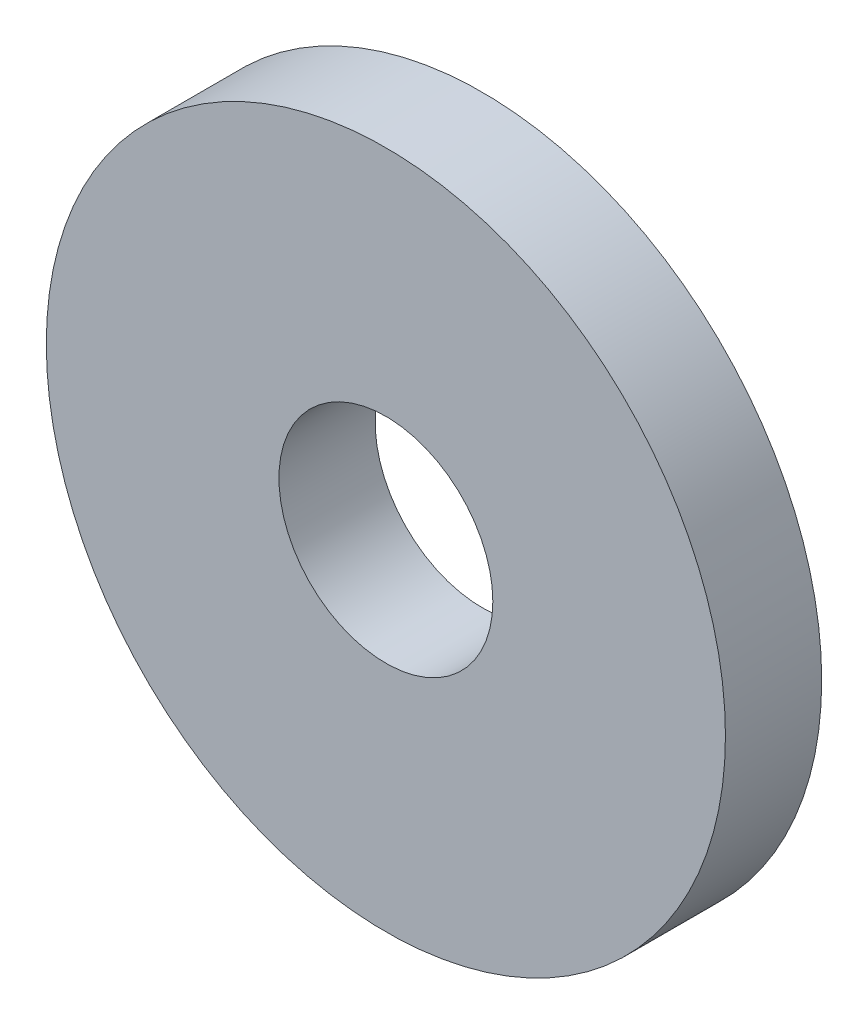
SolidWorks part; units mm, degrees
ref_plane "Front Plane" through (0, 0, 0) normal (0, 0, 1) x (1, 0, 0)
ref_plane "Top Plane" through (0, 0, 0) normal (0, 1, 0) x (1, 0, 0)
ref_plane "Right Plane" through (0, 0, 0) normal (1, 0, 0) x (0, 0, -1)
sketch "Sketch1" plane through (0, 0, 0) normal (0, 0, 1) x (1, 0, 0)
  circle A0 centre (0, 0) radius 15.875
  circle A1 centre (0, 0) radius 5
  dimension "D1" = 31.75
  dimension "D2" = 10
extrude "Boss-Extrude1" add sketch "Sketch1" along normal mid plane 4.5
